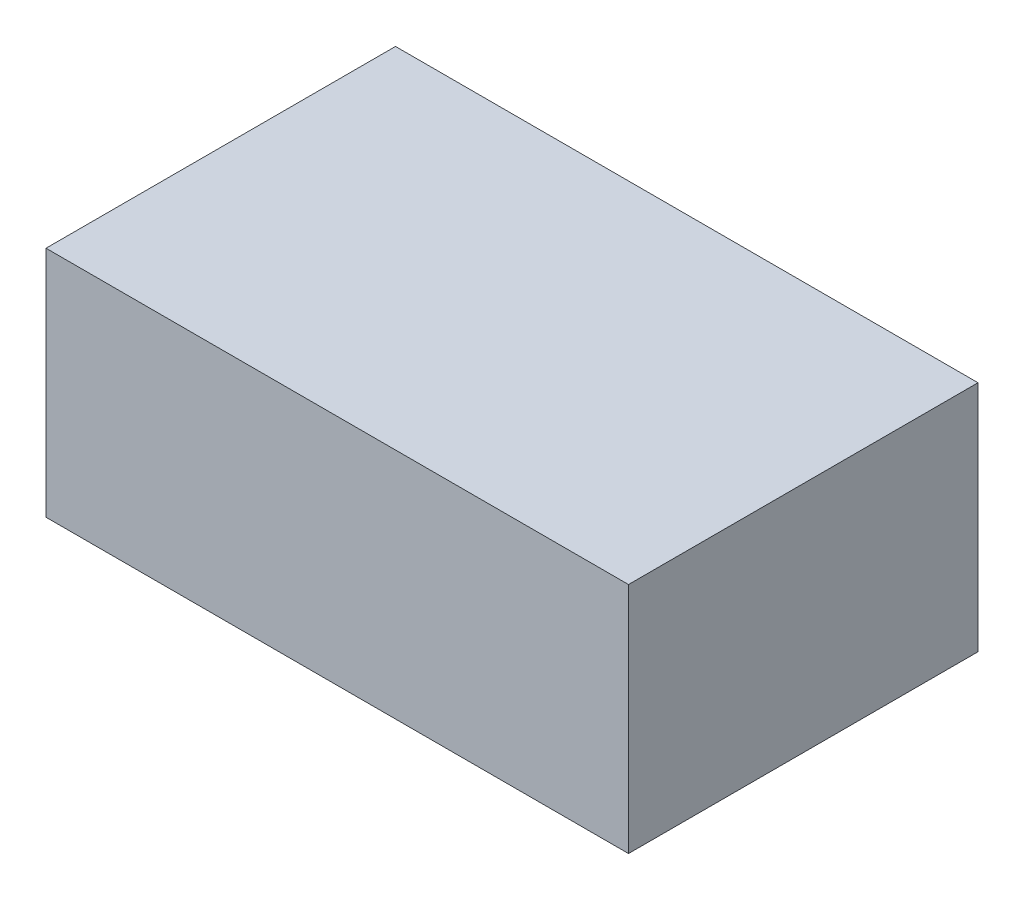
SolidWorks part; units mm, degrees
ref_plane "Alzado" through (0, 0, 0) normal (0, 0, 1) x (1, 0, 0)
ref_plane "Planta" through (0, 0, 0) normal (0, 1, 0) x (1, 0, 0)
ref_plane "Vista lateral" through (0, 0, 0) normal (1, 0, 0) x (0, 0, -1)
sketch "Croquis_base" plane through (0, 0, 0) normal (0, 1, 0) x (1, 0, 0)
  line L1 (-62.5, -37.5) -> (62.5, -37.5)
  line L2 (-62.5, -37.5) -> (-62.5, 37.5)
  line L3 (-62.5, 37.5) -> (62.5, 37.5)
  line L4 (62.5, -37.5) -> (62.5, 37.5)
  line L5 (-62.5, -37.5) -> (62.5, 37.5) construction
  line L6 (-62.5, 37.5) -> (62.5, -37.5) construction
  point P0 (0, 0)
  dimension "D1" = 62.5
  dimension "D2" = 37.5
extrude "Caja_baja" add sketch "Croquis_base" along normal blind 50
sketch "Croquis_agujeros_montaje" plane through (0, 0, 0) normal (0, 1, 0) x (1, 0, 0)
  circle A0 centre (-50, 0) radius 4
  circle A1 centre (50, 0) radius 4
  dimension "D1" = 8
  dimension "D2" = 100
extrude "Agujero_inserto_M6" cut sketch "Croquis_agujeros_montaje" along normal blind 14
